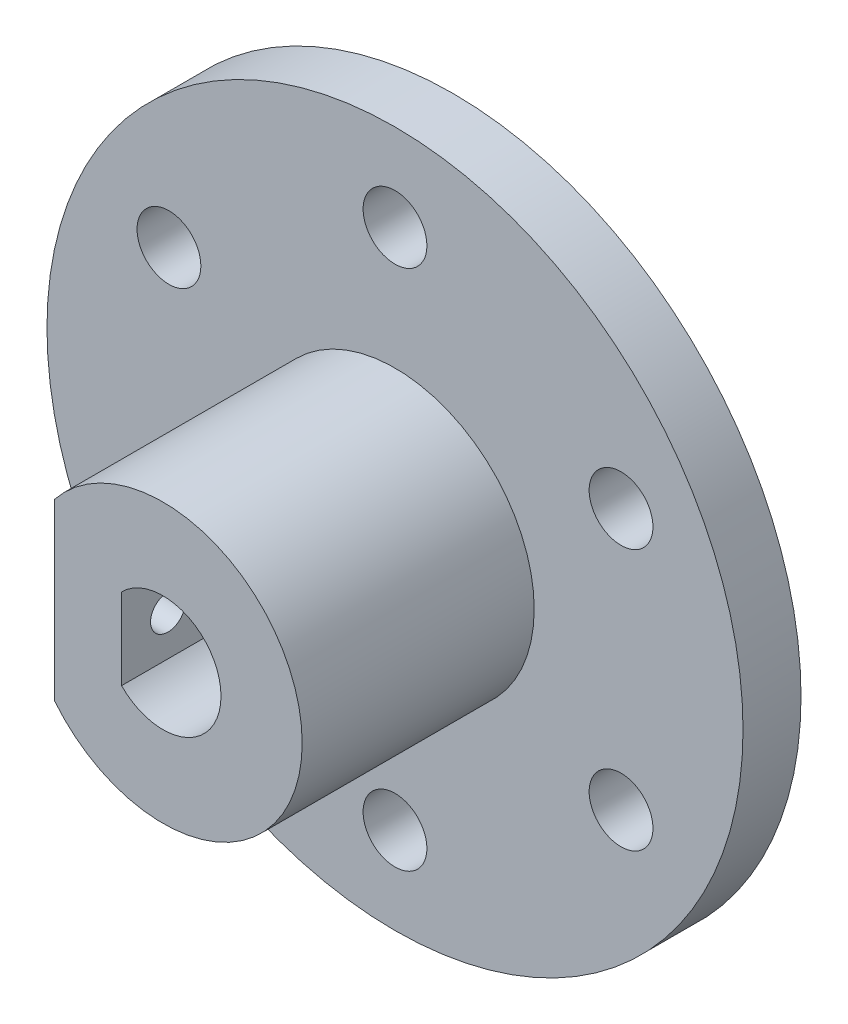
SolidWorks part; units mm, degrees
ref_plane "前视基准面" through (0, 0, 0) normal (0, 0, 1) x (1, 0, 0)
ref_plane "上视基准面" through (0, 0, 0) normal (0, 1, 0) x (1, 0, 0)
ref_plane "右视基准面" through (0, 0, 0) normal (1, 0, 0) x (0, 0, -1)
sketch "草图1" plane through (0, 0, 0) normal (0, 0, 1) x (1, 0, 0)
  circle A0 centre (0, 0) radius 30
  circle A1 centre (0, 0) radius 22.5 construction
  circle A2 centre (0, 22.5) radius 2.75
  circle A3 centre (19.4856, 11.25) radius 2.75
  circle A4 centre (19.4856, -11.25) radius 2.75
  circle A5 centre (0, -22.5) radius 2.75
  circle A6 centre (-19.4856, -11.25) radius 2.75
  circle A7 centre (-19.4856, 11.25) radius 2.75
  point P19 (0, 0)
  dimension "D1" = 60
  dimension "D2" = 45
  dimension "D3" = 5.5
  dimension "D4" = 6
extrude "凸台-拉伸1" add sketch "草图1" along normal blind 5
sketch "草图2" plane through (0, 0, 5) normal (0, 0, 1) x (1, 0, 0)
  line L0 (-9.3675, -7.5) -> (-9.3675, 7.5)
  line L1 (-3.5707, 3.5) -> (-3.5707, -3.5)
  arc A0 (-9.3675, -7.5) -> (-9.3675, 7.5) centre (0, 0) ccw
  arc A1 (-3.5707, -3.5) -> (-3.5707, 3.5) centre (0, 0) ccw
  dimension "D1" = 24
  dimension "D3" = 10
  dimension "D2" = 15
  dimension "D4" = 7
extrude "凸台-拉伸2" add sketch "草图2" along normal blind 20
sketch "草图3" plane through (-9.3675, 0, 0) normal (-1, 0, 0) x (0, 0, 1)
  line L0 (25, 7.5) -> (25, -7.5) construction
  line L1 (5, 7.5) -> (5, -7.5) construction
  circle A0 centre (21, 0) radius 1.5
  circle A1 centre (15, 0) radius 1.5
  dimension "D1" = 3
  dimension "D2" = 4
  dimension "D3" = 10
extrude "切除-拉伸1" cut sketch "草图3" against normal blind 10
